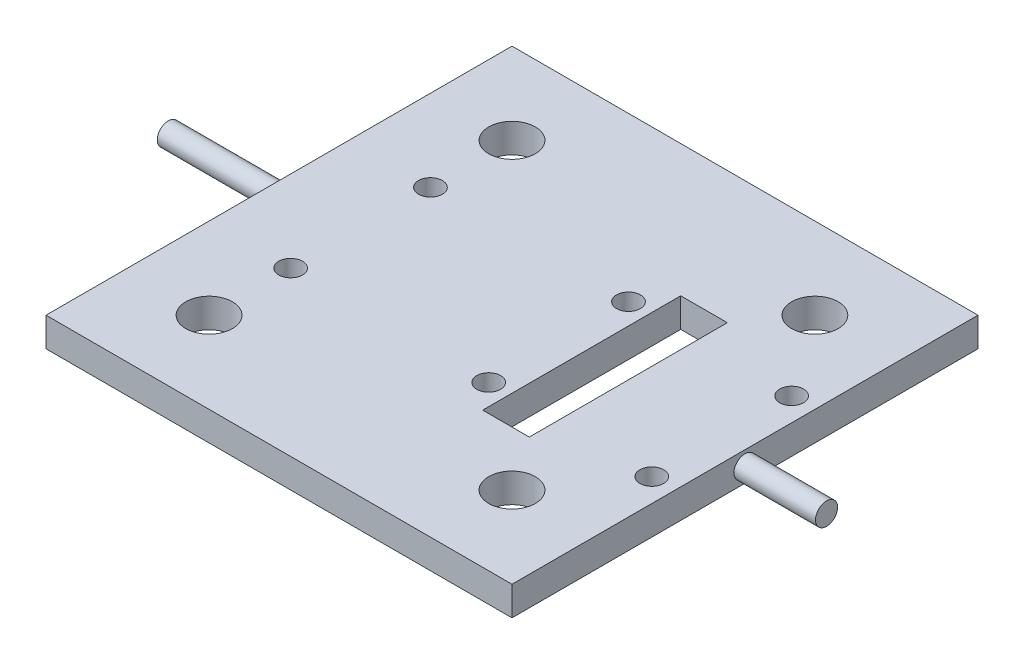
SolidWorks part; units mm, degrees
ref_plane "Front Plane" through (0, 0, 0) normal (0, 0, 1) x (1, 0, 0)
ref_plane "Top Plane" through (0, 0, 0) normal (0, 1, 0) x (1, 0, 0)
ref_plane "Right Plane" through (0, 0, 0) normal (1, 0, 0) x (0, 0, -1)
sketch "Sketch1" plane through (0, 0, 0) normal (0, 1, 0) x (1, 0, 0)
  line L1 (-25.4, -25.4) -> (25.4, -25.4)
  line L2 (-25.4, -25.4) -> (-25.4, 25.4)
  line L3 (-25.4, 25.4) -> (25.4, 25.4)
  line L4 (25.4, -25.4) -> (25.4, 25.4)
  line L5 (-25.4, -25.4) -> (25.4, 25.4) construction
  line L6 (-25.4, 25.4) -> (25.4, -25.4) construction
  point P0 (0, 0)
  dimension "D1" = 50.8
extrude "Boss-Extrude1" add sketch "Sketch1" along normal mid plane 3.175
sketch "Sketch3" plane through (25.4, 0, 0) normal (1, 0, 0) x (0, 0, -1)
  circle A0 centre (0, 0) radius 1.2065
  dimension "D1" = 2.413
extrude "Boss-Extrude2" add sketch "Sketch3" along normal blind 8.89
sketch "Sketch4" plane through (0, 1.5875, 0) normal (0, 1, 0) x (1, 0, 0)
  line L0 (25.4, 25.4) -> (-25.4, 25.4) construction
  line L1 (-25.4, 25.4) -> (-25.4, -25.4) construction
  line L2 (25.4, -25.4) -> (25.4, 25.4) construction
  line L3 (25.4, -25.4) -> (25.4, 25.4) construction
  line L4 (-25.4, -25.4) -> (25.4, -25.4) construction
  line L5 (-25.4, 25.4) -> (-25.4, -25.4) construction
  line L6 (-25.4, 0) -> (25.4, 0) construction
  line L7 (0, 25.4) -> (0, -25.4) construction
  line L8 (25.4, 25.4) -> (-25.4, 25.4) construction
  line L12 (-25.4, 25.4) -> (-25.4, -25.4) construction
  line L14 (25.4, -25.4) -> (25.4, 25.4) construction
  circle A1 centre (-16.51, 16.51) radius 2.54
  circle A2 centre (16.51, 16.51) radius 2.54
  circle A3 centre (16.51, -16.51) radius 2.54
  circle A4 centre (-16.51, -16.51) radius 2.54
  point P0 (-16.51, -7.62)
  point P1 (-16.51, 7.62)
  point P2 (0, 0)
  point P13 (22.86, 7.62)
  point P14 (22.86, -7.62)
  point P66 (0, 0)
  point P68 (-25.4, 0)
  point P71 (25.4, 0)
  dimension "D1" = 5.08
  dimension "D2" = 8.89
  dimension "D3" = 8.89
  dimension "D4" = 8.89
  dimension "D5" = 8.89
  dimension "D6" = 8.89
  dimension "D7" = 8.89
  dimension "D8" = 8.89
  dimension "D9" = 8.89
  dimension "D10" = 8.89
  dimension "D11" = 17.78
  dimension "D12" = 8.89
  dimension "D13" = 17.78
  dimension "D14" = 15.24
  dimension "D15" = 17.78
  dimension "D16" = 2.54
extrude "Cut-Extrude1" cut sketch "Sketch4" against normal through all
sketch "Sketch5" plane through (-25.4, 0, 0) normal (-1, 0, 0) x (0, 0, 1)
  circle A0 centre (0, 0) radius 1.2065
  dimension "D1" = 2.413
extrude "Boss-Extrude3" add sketch "Sketch5" along normal blind 12.065
hole_wizard "M2 Clearance Hole1" positions "Sketch6" profile "Sketch7" hole size "M2" standard "ANSI Metric" end condition through all
sketch "Sketch6" plane through (0, 1.5875, 0) normal (0, 1, 0) x (1, 0, 0)
  line L0 (25.4, -25.4) -> (25.4, 25.4) construction
  point P0 (-16.51, -7.62)
  point P3 (-16.51, 7.62)
  point P7 (5.08, -7.62)
  point P10 (5.08, 7.62)
  point P13 (22.86, 7.62)
  point P15 (22.86, -7.62)
  dimension "D1" = 2.54
  dimension "D2" = 2.54
sketch "Sketch7" plane through (-16.51, 1.5875, 7.62) normal (1, 0, 0) x (0, 0, 1)
  line L0 (0, 0) -> (0, 3.175)
  line L1 (0, 3.175) -> (1.3, 3.175)
  line L2 (1.3, 3.175) -> (1.3, 0)
  line L5 (1.3, 0) -> (0, 0)
  line L11 (0, -6.35) -> (0, 107.95) construction
  dimension "Thru Hole Dia." = 2.6
  dimension "Thru Hole Depth" = 3.175
sketch "Sketch8" plane through (0, 1.5875, 0) normal (0, 1, 0) x (1, 0, 0)
  line L0 (25.4, -25.4) -> (25.4, 25.4) construction
  line L1 (12.446, -10.5628) -> (7.366, -10.5628)
  line L2 (12.446, -10.5628) -> (12.446, 11.0272)
  line L3 (12.446, 11.0272) -> (7.366, 11.0272)
  line L4 (7.366, -10.5628) -> (7.366, 11.0272)
  line L5 (12.446, -10.5628) -> (7.366, 11.0272) construction
  line L6 (12.446, 11.0272) -> (7.366, -10.5628) construction
  point P0 (9.906, 0.2322)
  point P7 (0, 0)
  dimension "D1" = 5.08
  dimension "D2" = 21.59
  dimension "D3" = 12.954
extrude "Cut-Extrude2" cut sketch "Sketch8" against normal up to next
